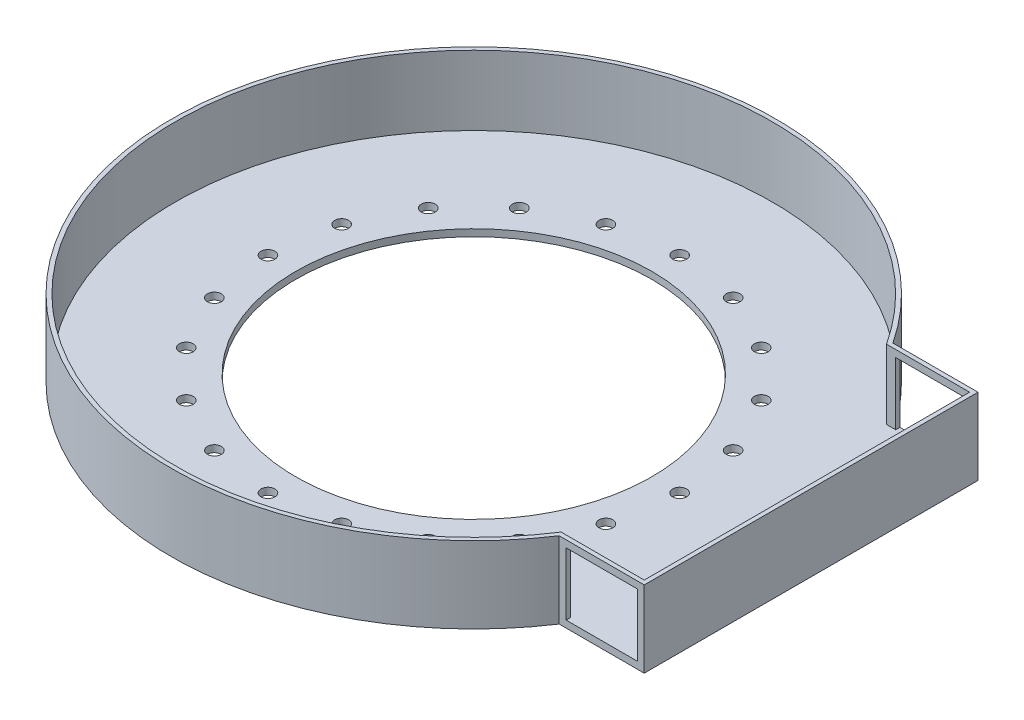
SolidWorks part; units mm, degrees
ref_plane "Plan de face" through (0, 0, 0) normal (0, 0, 1) x (1, 0, 0)
ref_plane "Plan de dessus" through (0, 0, 0) normal (0, 1, 0) x (1, 0, 0)
ref_plane "Plan de droite" through (0, 0, 0) normal (1, 0, 0) x (0, 0, -1)
sketch "Esquisse1" plane through (0, 0, 0) normal (0, 0, 1) x (1, 0, 0)
  line L0 (0, 0) -> (256, 0) construction
  line L1 (0, 0) -> (0, 51.0849) construction
  line L2 (256, 0) -> (336, 0)
  line L3 (256, 0) -> (256, 10)
  line L4 (256, 10) -> (336, 10)
  line L5 (336, 0) -> (336, 10)
  dimension "D1" = 80
  dimension "D2" = 10
  dimension "D3" = 256
revolve "Révolution1" add sketch "Esquisse1" angle 360 about L1
sketch "Esquisse3" plane through (0, 10, 0) normal (0, 1, 0) x (1, 0, 0)
  circle A0 centre (296, 0) radius 10
  dimension "D1" = 20
  dimension "D2" = 296
extrude "Enlèv. mat.-Extru.1" cut sketch "Esquisse3" against normal through all
pattern_circular "Répétition circulaire1" count 20 over 360 about axis through (0, 0, 0) along (0, 1, 0) of "Enlèv. mat.-Extru.1"
sketch "Esquisse4" plane through (0, 0, 0) normal (0, -1, 0) x (1, 0, 0)
  line L0 (0, 0) -> (538.9638, 0) construction
  line L1 (485.151, -240) -> (485.151, 240)
  line L2 (485.151, 240) -> (235.151, 240)
  line L4 (235.151, -240) -> (485.151, -240)
  circle A0 centre (0, 0) radius 336 construction
  arc A1 (235.151, -240) -> (235.151, 240) centre (0, 0) ccw
  point P6 (485.151, 0)
  dimension "D1" = 250
  dimension "D2" = 480
extrude "Boss.-Extru.1" add sketch "Esquisse4" against normal blind 10
sketch "Esquisse5" plane through (0, 0, 0) normal (0, -1, 0) x (1, 0, 0)
  line L0 (235.151, -240) -> (485.151, -240) construction
  line L1 (485.151, 240) -> (235.151, 240) construction
  line L2 (235.151, -240) -> (362.8016, -240)
  line L3 (362.8016, 240) -> (235.151, 240)
  arc A0 (362.8016, 240) -> (362.8016, -240) centre (0, 0) ccw
  arc A1 (235.151, 240) -> (235.151, -240) centre (0, 0) ccw construction
  arc A2 (235.151, 240) -> (235.151, -240) centre (0, 0) ccw
  dimension "D1" = 435
extrude "Boss.-Extru.2" add sketch "Esquisse5" against normal blind 10
sketch "Esquisse6" plane through (0, 10, 0) normal (0, 1, 0) x (1, 0, 0)
  line L6 (359.5622, -234) -> (479.151, -234)
  line L7 (479.151, -234) -> (479.151, 234)
  line L8 (479.151, 234) -> (359.5622, 234)
  line L9 (359.5622, -234) -> (479.151, -234)
  line L10 (479.151, -234) -> (479.151, 234)
  line L11 (479.151, 234) -> (359.5622, 234)
  arc A2 (359.5622, 234) -> (359.5622, -234) centre (0, 0) ccw
  arc A3 (359.5622, 234) -> (359.5622, -234) centre (0, 0) ccw
  arc M5 (362.8016, 240) -> (362.8016, -240) centre (0, 0) ccw
  line M6 (362.8016, -240) -> (485.151, -240)
  line M7 (485.151, -240) -> (485.151, 240)
  line M8 (485.151, 240) -> (362.8016, 240)
  dimension "D1" = 6
extrude "Boss.-Extru.3" add sketch "Esquisse6" along normal blind 100 contours A3 L11 L10 L9 M8 M5 M6 M7
sketch "Esquisse8" plane through (0, 0, 240) normal (0, 0, 1) x (1, 0, 0)
  line L8 (372.8016, 100) -> (372.8016, 10)
  line L9 (372.8016, 10) -> (475.151, 10)
  line L10 (475.151, 10) -> (475.151, 100)
  line L11 (475.151, 100) -> (372.8016, 100)
  line L12 (372.8016, 100) -> (372.8016, 10)
  line L13 (372.8016, 10) -> (475.151, 10)
  line L14 (475.151, 10) -> (475.151, 100)
  line L15 (475.151, 100) -> (372.8016, 100)
  dimension "D1" = 10
extrude "Enlèv. mat.-Extru.2" cut sketch "Esquisse8" against normal through all
